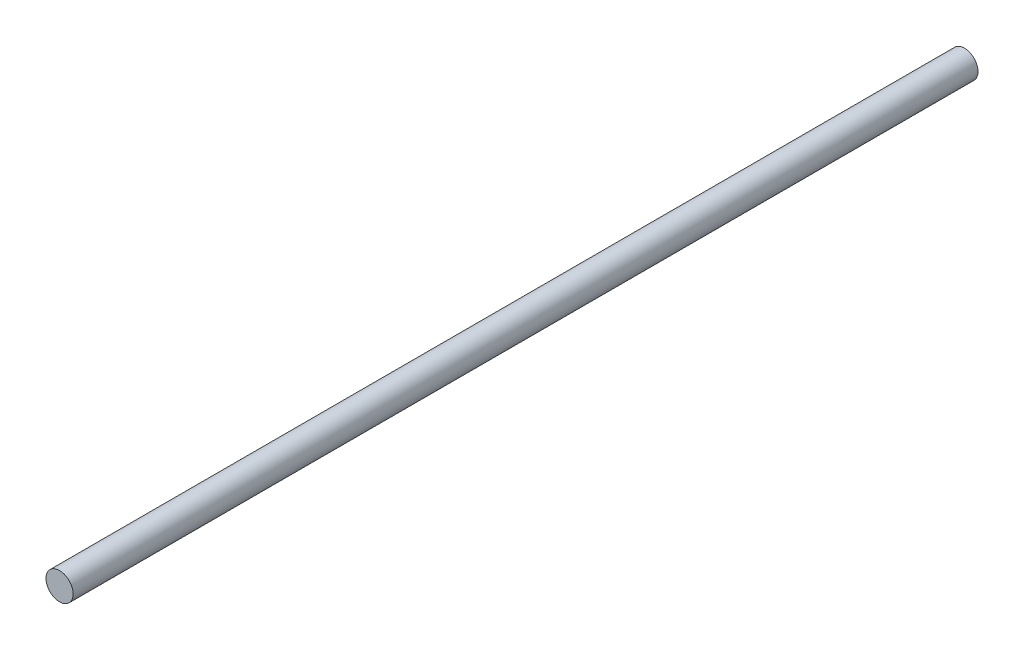
SolidWorks part; units mm, degrees
ref_plane "前视基准面" through (0, 0, 0) normal (0, 0, 1) x (1, 0, 0)
ref_plane "上视基准面" through (0, 0, 0) normal (0, 1, 0) x (1, 0, 0)
ref_plane "右视基准面" through (0, 0, 0) normal (1, 0, 0) x (0, 0, -1)
sketch "草图1" plane through (0, 0, 0) normal (0, 0, 1) x (1, 0, 0)
  circle A0 centre (0, 0) radius 1.5
  dimension "D1" = 3
extrude "凸台-拉伸1" add sketch "草图1" along normal blind 100
